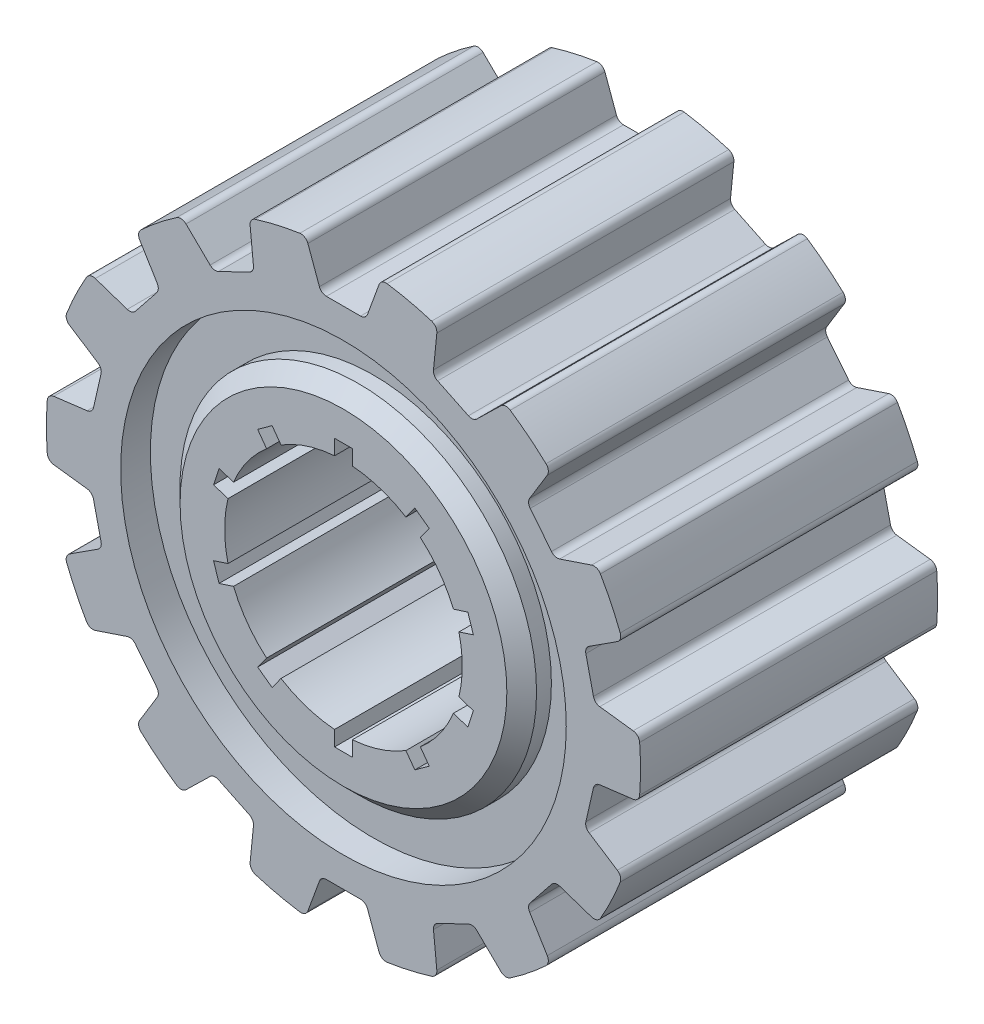
SolidWorks part; units mm, degrees
ref_plane "Front Plane" through (0, 0, 0) normal (0, 0, 1) x (1, 0, 0)
ref_plane "Top Plane" through (0, 0, 0) normal (0, 1, 0) x (1, 0, 0)
ref_plane "Right Plane" through (0, 0, 0) normal (1, 0, 0) x (0, 0, -1)
sketch "Sketch1" plane through (0, 0, 0) normal (0, 0, 1) x (1, 0, 0)
  line L0 (2.4023, 3.8169) -> (2.1018, 3.4033)
  line L1 (-0.3, 4.5) -> (0.3, 4.5)
  line L2 (-0.3, 4.5) -> (-0.3, 3.9887)
  line L4 (0.3, 4.5) -> (0.3, 3.9887)
  line L5 (2.4023, 3.8169) -> (2.8877, 3.4642)
  line L6 (2.8877, 3.4642) -> (2.5872, 3.0506)
  line L7 (4.187, 1.6759) -> (3.7008, 1.5179)
  line L8 (4.187, 1.6759) -> (4.3725, 1.1053)
  line L9 (4.3725, 1.1053) -> (3.8862, 0.9473)
  line L10 (4.3725, -1.1053) -> (3.8862, -0.9473)
  line L11 (4.3725, -1.1053) -> (4.187, -1.6759)
  line L12 (4.187, -1.6759) -> (3.7008, -1.5179)
  line L13 (2.8877, -3.4642) -> (2.5872, -3.0506)
  line L14 (2.8877, -3.4642) -> (2.4023, -3.8169)
  line L15 (2.4023, -3.8169) -> (2.1018, -3.4033)
  line L16 (0.3, -4.5) -> (0.3, -3.9887)
  line L17 (0.3, -4.5) -> (-0.3, -4.5)
  line L18 (-0.3, -4.5) -> (-0.3, -3.9887)
  line L19 (-2.4023, -3.8169) -> (-2.1018, -3.4033)
  line L20 (-2.4023, -3.8169) -> (-2.8877, -3.4642)
  line L21 (-2.8877, -3.4642) -> (-2.5872, -3.0506)
  line L22 (-4.187, -1.6759) -> (-3.7008, -1.5179)
  line L23 (-4.187, -1.6759) -> (-4.3725, -1.1053)
  line L24 (-4.3725, -1.1053) -> (-3.8862, -0.9473)
  line L25 (-4.3725, 1.1053) -> (-3.8862, 0.9473)
  line L26 (-4.3725, 1.1053) -> (-4.187, 1.6759)
  line L27 (-4.187, 1.6759) -> (-3.7008, 1.5179)
  line L28 (-2.8877, 3.4642) -> (-2.5872, 3.0506)
  line L29 (-2.8877, 3.4642) -> (-2.4023, 3.8169)
  line L30 (-2.4023, 3.8169) -> (-2.1018, 3.4033)
  circle A0 centre (0, 0) radius 10
  arc A1 (-0.3, 3.9887) -> (-2.1018, 3.4033) centre (0, 0) ccw
  arc A2 (-2.5872, 3.0506) -> (-3.7008, 1.5179) centre (0, 0) ccw
  arc A3 (3.7008, 1.5179) -> (0.3, 3.9887) centre (0, 0) ccw
  arc A4 (3.8862, -0.9473) -> (3.8862, 0.9473) centre (0, 0) ccw
  arc A5 (2.5872, -3.0506) -> (3.7008, -1.5179) centre (0, 0) ccw
  arc A6 (0.3, -3.9887) -> (2.1018, -3.4033) centre (0, 0) ccw
  arc A7 (-2.1018, -3.4033) -> (-0.3, -3.9887) centre (0, 0) ccw
  arc A8 (-3.7008, -1.5179) -> (-2.5872, -3.0506) centre (0, 0) ccw
  arc A9 (-3.8862, 0.9473) -> (-3.8862, -0.9473) centre (0, 0) ccw
  point P4 (0, 4)
  point P46 (0, 0)
  dimension "D1" = 20
  dimension "D2" = 8
  dimension "D3" = 0.6
  dimension "D4" = 4.5
  dimension "D5" = 0.5113
  dimension "D6" = 10
extrude "Boss-Extrude1" add sketch "Sketch1" along normal blind 10 contours A0 A9 L25 L26 L27 A2 L28 L29 L30 A1 L2 L1 L4 A3 L0 L5 L6 L7 L8 L9 A4 L10 L11 L12 A5 L13 L14 L15 A6 L16 L17 L18 A7 L19 L20 L21 A8 L22 L23 L24
sketch "Sketch2" plane through (0, 0, 10) normal (0, 0, 1) x (1, 0, 0)
  line L0 (0, 10) -> (0, 0) construction
  line L1 (-0.75, 8.5) -> (0.75, 8.5)
  line L2 (0.75, 8.5) -> (1.2666, 9.9195)
  line L3 (-0.75, 8.5) -> (-1.2666, 9.9195)
  circle A0 centre (0, 0) radius 10 construction
  arc A1 (-1.2666, 9.9195) -> (1.2666, 9.9195) centre (0, 9.116) cw
  point P10 (0, 8.5)
  dimension "D4" = 1.5
  dimension "D1" = 0.75
  dimension "D2" = 20
  dimension "D3" = 8.5
extrude "Cut-Extrude1" cut sketch "Sketch2" against normal through all
pattern_circular "CirPattern1" count 14 over 360 about axis through (0, 0, 0) along (0, 0, 1) of "Cut-Extrude1"
sketch "Sketch4" plane through (0, 0, 10) normal (0, 0, 1) x (1, 0, 0)
  circle A0 centre (0, 0) radius 7.5
  circle A1 centre (0, 0) radius 6
  dimension "D1" = 15
  dimension "D2" = 12
extrude "Cut-Extrude2" cut sketch "Sketch4" against normal blind 1
chamfer "Chamfer1" distance 0.5 angle 45 1 edges at (6, 0, 10)
ref_plane "Plane1" through (0, 0, 5) normal (0, 0, 1) x (1, 0, 0)
sketch "Sketch6" plane through (0, 0, 0) normal (0, 0, -1) x (-1, 0, 0)
  circle A0 centre (0, 0) radius 7.5
  circle A1 centre (0, 0) radius 6
  dimension "D1" = 15
  dimension "D2" = 12
extrude "Cut-Extrude4" cut sketch "Sketch6" against normal blind 1
chamfer "Chamfer2" distance 0.5 angle 45 1 edges at (-6, 0, 0)
fillet "Fillet1" radius 0.25 56 edges at (-7.1132, 4.7133, 5) (-8.5451, 5.1944, 5) (-9.3889, 3.4422, 5) (-8.12, 2.6226, 5) (-8.4538, 1.1602, 5) (-9.9526, 0.9724, 5) (-9.9526, -0.9724, 5) (-8.4538, -1.1602, 5) (-8.12, -2.6226, 5) (-9.3889, -3.4422, 5) (-8.5451, -5.1944, 5) (-7.1132, -4.7133, 5) (-6.178, -5.886, 5) (-6.9656, -7.175, 5) (-5.4451, -8.3875, 5) (-4.3637, -7.3328, 5) (-3.0123, -7.9836, 5) (-3.1627, -9.4867, 5) (-1.2666, -9.9195, 5) (-0.75, -8.5, 5) (0.75, -8.5, 5) (1.2666, -9.9195, 5) (3.1627, -9.4867, 5) (3.0123, -7.9836, 5) (4.3637, -7.3328, 5) (5.4451, -8.3875, 5) (6.9656, -7.175, 5) (6.178, -5.886, 5) (7.1132, -4.7133, 5) (8.5451, -5.1944, 5) (9.3889, -3.4422, 5) (8.12, -2.6226, 5) (8.4538, -1.1602, 5) (9.9526, -0.9724, 5) (9.9526, 0.9724, 5) (8.4538, 1.1602, 5) (8.12, 2.6226, 5) (9.3889, 3.4422, 5) (8.5451, 5.1944, 5) (7.1132, 4.7133, 5) (6.178, 5.886, 5) (5.4451, 8.3875, 5) (4.3637, 7.3328, 5) (3.0123, 7.9836, 5) (3.1627, 9.4867, 5) (1.2666, 9.9195, 5) (0.75, 8.5, 5) (-0.75, 8.5, 5) (-1.2666, 9.9195, 5) (-3.1627, 9.4867, 5) (-3.0123, 7.9836, 5) (-4.3637, 7.3328, 5) (-5.4451, 8.3875, 5) (-6.9656, 7.175, 5) (-6.178, 5.886, 5) (6.9656, 7.175, 5)
